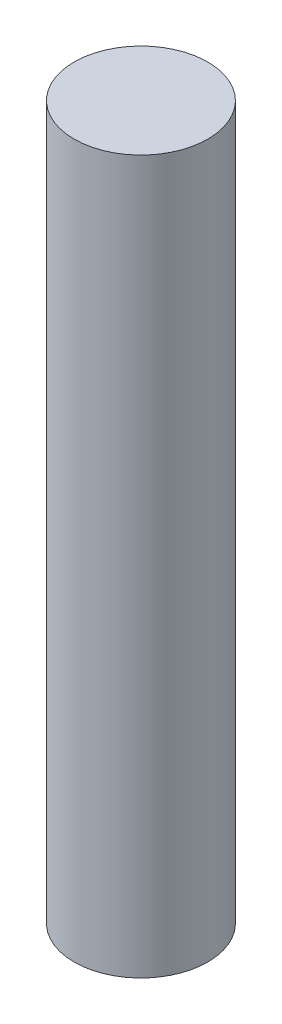
SolidWorks part; units mm, degrees
ref_plane "Front Plane" through (0, 0, 0) normal (0, 0, 1) x (1, 0, 0)
ref_plane "Top Plane" through (0, 0, 0) normal (0, 1, 0) x (1, 0, 0)
ref_plane "Right Plane" through (0, 0, 0) normal (1, 0, 0) x (0, 0, -1)
sketch "Sketch4" plane through (0, 0, 0) normal (0, 1, 0) x (1, 0, 0)
  circle A0 centre (0, 0) radius 9.525
  dimension "D1" = 19.05
extrude "Boss-Extrude2" add sketch "Sketch4" along normal blind 101.6
cosmetic thread "Cosmetic Thread3" parameters "D1"=50.72, "D2"=17.178
